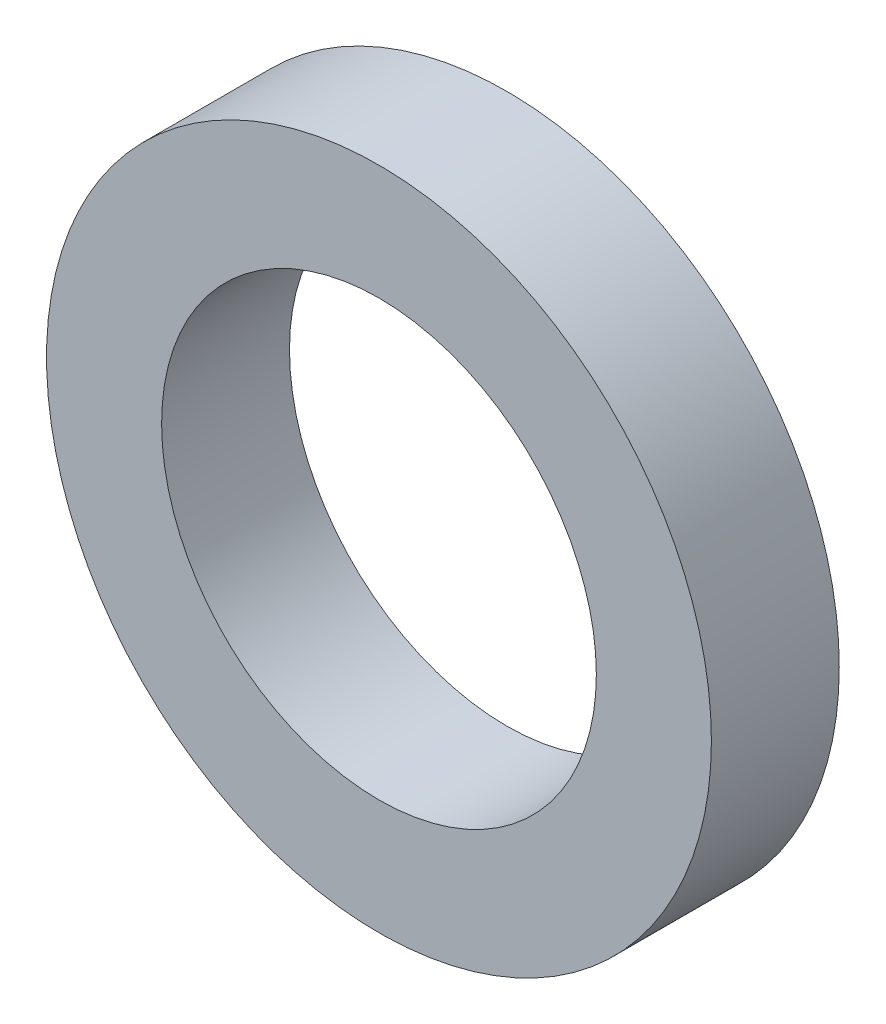
SolidWorks part; units mm, degrees
ref_plane "Спереди" through (0, 0, 0) normal (0, 0, 1) x (1, 0, 0)
ref_plane "Сверху" through (0, 0, 0) normal (0, 1, 0) x (1, 0, 0)
ref_plane "Справа" through (0, 0, 0) normal (1, 0, 0) x (0, 0, -1)
sketch "Эскиз1" plane through (0, 0, 0) normal (0, 0, 1) x (1, 0, 0)
  circle A0 centre (0, 0) radius 13
  circle A1 centre (0, 0) radius 8.5
extrude "Bearing6803" add sketch "Эскиз1" along normal blind 5 from offset 20
